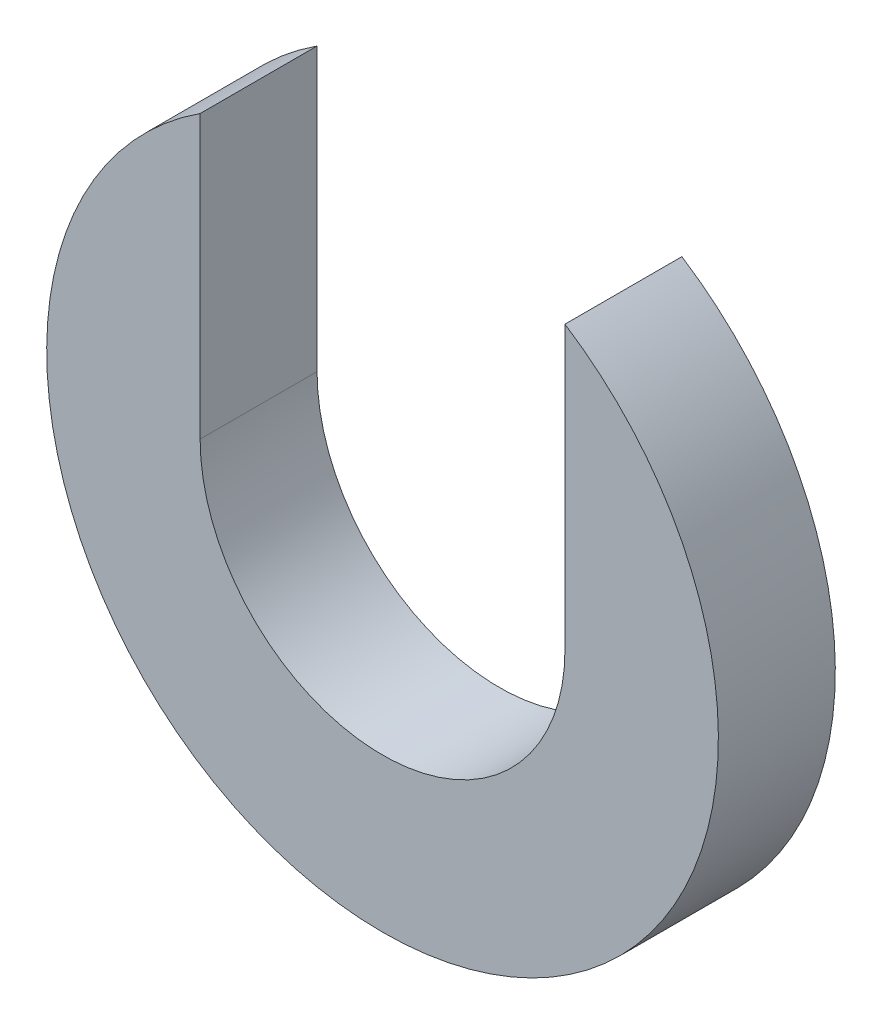
SolidWorks part; units mm, degrees
ref_plane "Front Plane" through (0, 0, 0) normal (0, 0, 1) x (1, 0, 0)
ref_plane "Top Plane" through (0, 0, 0) normal (0, 1, 0) x (1, 0, 0)
ref_plane "Right Plane" through (0, 0, 0) normal (1, 0, 0) x (0, 0, -1)
sketch "Sketch1" plane through (0, 0, 0) normal (0, 0, 1) x (1, 0, 0)
  line L0 (-4.953, 7.6562) -> (-4.953, 0)
  line L1 (4.953, 7.6562) -> (4.953, 0)
  arc A0 (-4.953, 7.6562) -> (4.953, 7.6562) centre (0, 0) ccw
  arc A1 (-4.953, 0) -> (4.953, 0) centre (0, 0) ccw
  dimension "D1" = 9.1186
  dimension "D2" = 9.906
extrude "Boss-Extrude1" add sketch "Sketch1" along normal blind 3.175
